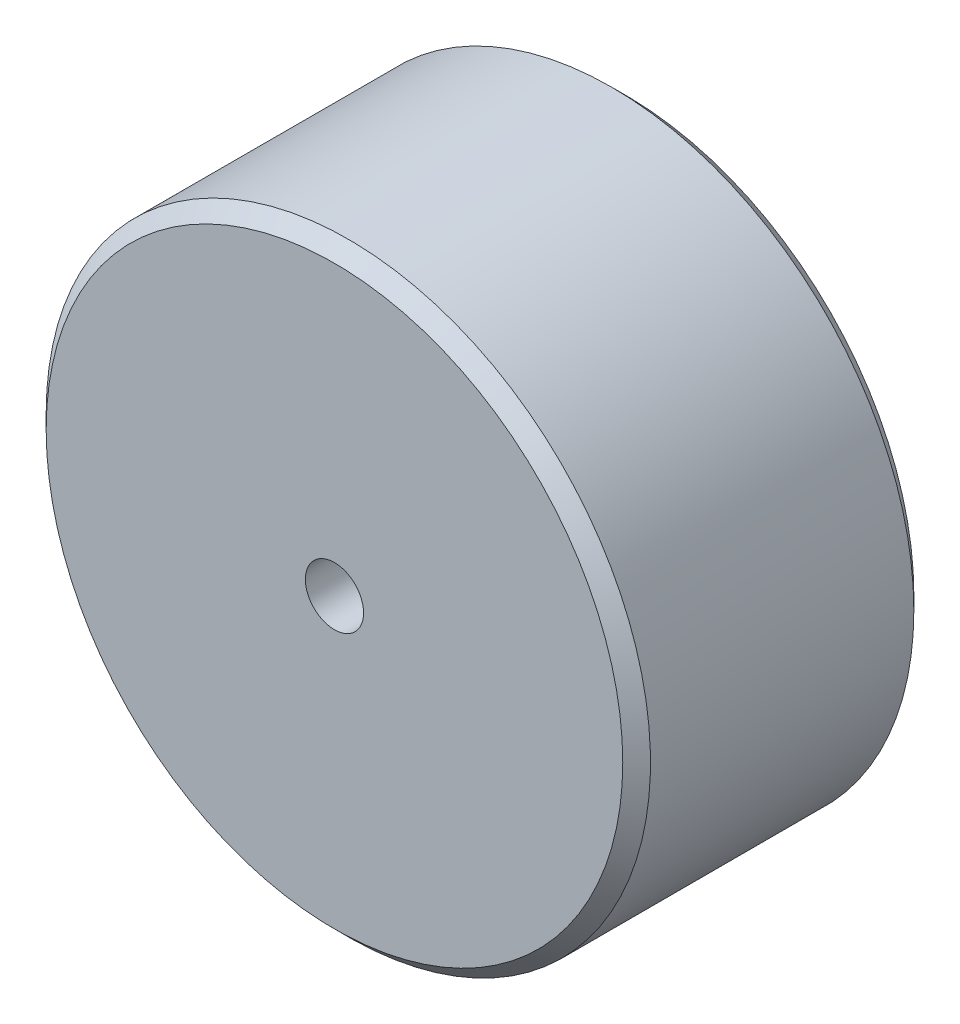
SolidWorks part; units mm, degrees
ref_plane "Front Plane" through (0, 0, 0) normal (0, 0, 1) x (1, 0, 0)
ref_plane "Top Plane" through (0, 0, 0) normal (0, 1, 0) x (1, 0, 0)
ref_plane "Right Plane" through (0, 0, 0) normal (1, 0, 0) x (0, 0, -1)
sketch "Sketch1" plane through (0, 0, 0) normal (0, 0, 1) x (1, 0, 0)
  circle A0 centre (0, 0) radius 21.8
  dimension "D1" = 43.6
extrude "Boss-Extrude1" add sketch "Sketch1" along normal blind 21
sketch "Sketch2" plane through (0, 0, 21) normal (0, 0, 1) x (1, 0, 0)
  circle A0 centre (0, 0) radius 2.1
  dimension "D1" = 4.2
chamfer "Chamfer1" distance 1 angle 45 2 edges at (21.8, 0, 21) (21.8, 0, 0)
extrude "Cut-Extrude1" cut sketch "Sketch2" against normal blind 5.8
